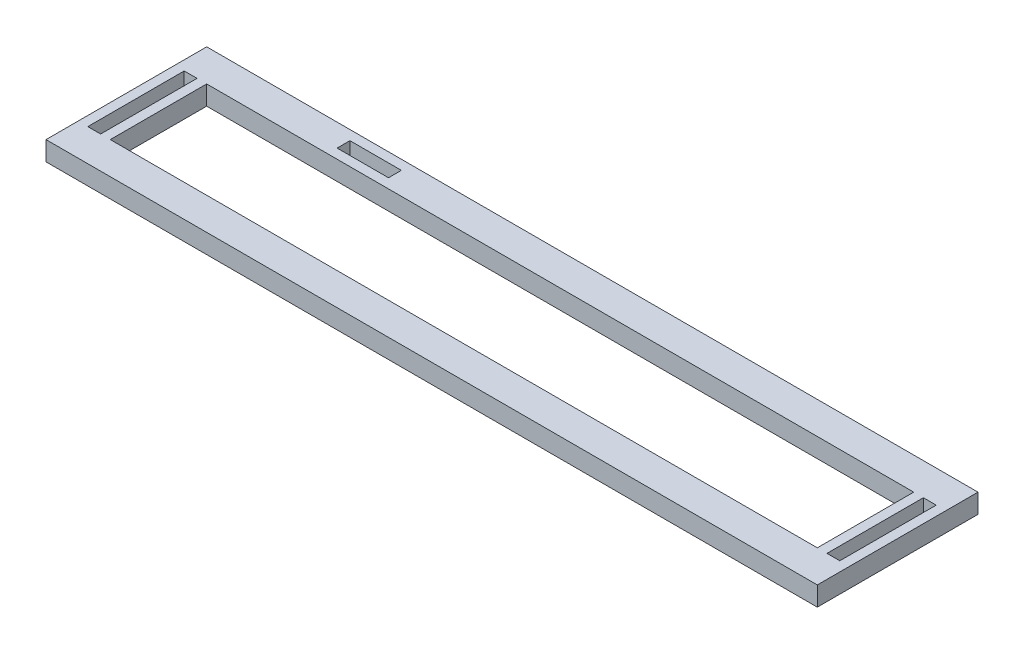
SolidWorks part; units mm, degrees
ref_plane "Front Plane" through (0, 0, 0) normal (0, 0, 1) x (1, 0, 0)
ref_plane "Top Plane" through (0, 0, 0) normal (0, 1, 0) x (1, 0, 0)
ref_plane "Right Plane" through (0, 0, 0) normal (1, 0, 0) x (0, 0, -1)
sketch "Sketch1" plane through (0, 0, 0) normal (0, 1, 0) x (1, 0, 0)
  line L0 (60, 20) -> (60, 5) construction
  line L1 (0, 0) -> (120, 0)
  line L2 (0, 0) -> (0, 25)
  line L3 (0, 25) -> (120, 25)
  line L4 (120, 0) -> (120, 25)
  line L5 (5, 20) -> (115, 20)
  line L6 (5, 20) -> (5, 5)
  line L7 (5, 5) -> (115, 5)
  line L8 (115, 20) -> (115, 5)
  line L9 (1.5, 20) -> (3.5, 20)
  line L10 (1.5, 20) -> (1.5, 5)
  line L11 (1.5, 5) -> (3.5, 5)
  line L12 (3.5, 20) -> (3.5, 5)
  line L13 (118.5, 5) -> (116.5, 5)
  line L14 (118.5, 20) -> (116.5, 20)
  line L15 (116.5, 20) -> (116.5, 5)
  line L16 (118.5, 20) -> (118.5, 5)
  line L18 (23.7875, 23.5) -> (31.7875, 23.5)
  line L19 (23.7875, 23.5) -> (23.7875, 21.5)
  line L20 (23.7875, 21.5) -> (31.7875, 21.5)
  line L21 (31.7875, 23.5) -> (31.7875, 21.5)
  dimension "D1" = 120
  dimension "D2" = 25
  dimension "D3" = 5
  dimension "D4" = 5
  dimension "D5" = 5
  dimension "D6" = 5
  dimension "D7" = 1.5
  dimension "D8" = 5
  dimension "D9" = 5
  dimension "D10" = 2
  dimension "D11" = 2
  dimension "D12" = 1.5
  dimension "D13" = 8
extrude "Boss-Extrude1" add sketch "Sketch1" along normal blind 3
